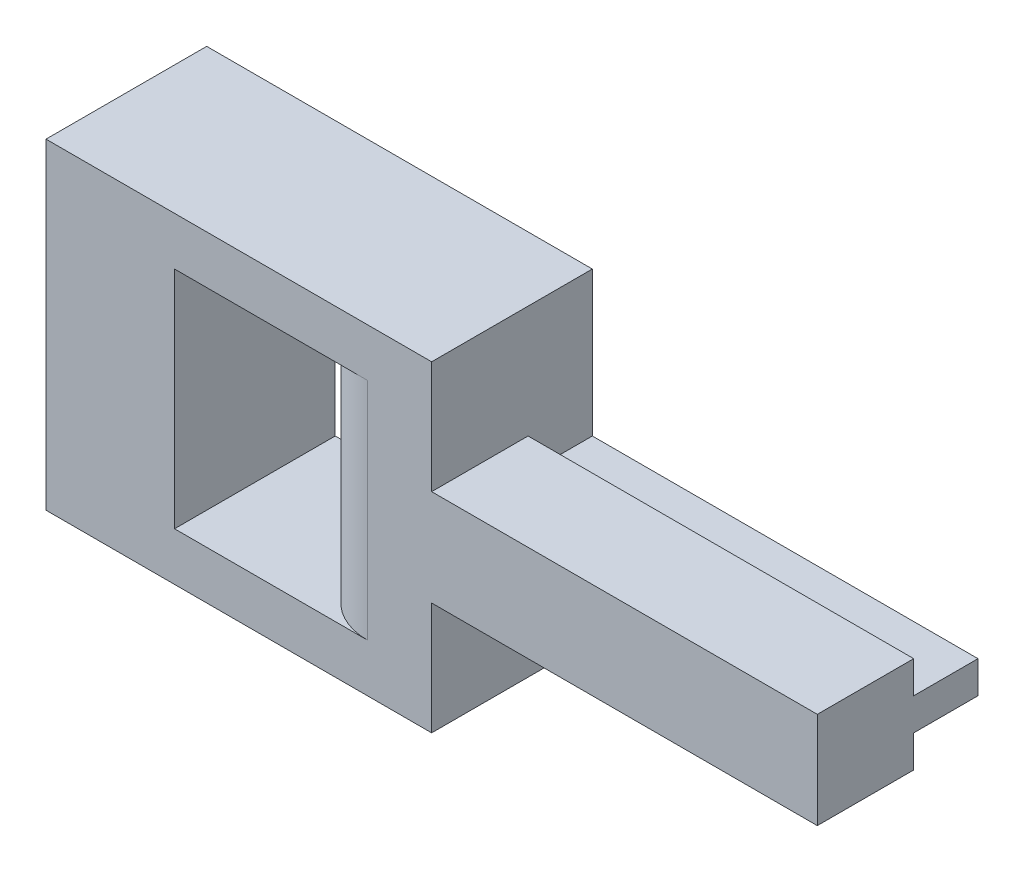
SolidWorks part; units mm, degrees
ref_plane "Plano frontal" through (0, 0, 0) normal (0, 0, 1) x (1, 0, 0)
ref_plane "Plano superior" through (0, 0, 0) normal (0, 1, 0) x (1, 0, 0)
ref_plane "Plano direito" through (0, 0, 0) normal (1, 0, 0) x (0, 0, -1)
sketch "Esboço1" plane through (0, 0, 0) normal (0, 0, 1) x (1, 0, 0)
  line L0 (4, 1.5) -> (8, 1.5)
  line L1 (24, 3.5) -> (24, 6.5)
  line L2 (4, 8.5) -> (8, 8.5)
  line L3 (8, 8.5) -> (8, 1.5)
  line L4 (0, 0) -> (12, 0)
  line L5 (4, 1.5) -> (4, 8.5)
  line L6 (12, 10) -> (0, 10)
  line L7 (0, 10) -> (0, 0)
  line L8 (12, 0) -> (12, 3.5)
  line L9 (12, 3.5) -> (24, 3.5)
  line L10 (12, 6.5) -> (12, 10)
  line L11 (12, 6.5) -> (24, 6.5)
  line L12 (24, 5) -> (9.8395, 5) construction
  point P1 (0, 5)
  point P19 (4, 5)
  dimension "D1" = 12
  dimension "D2" = 4
  dimension "D3" = 4
  dimension "D4" = 10
  dimension "D5" = 7
  dimension "D6" = 4
  dimension "D7" = 3
extrude "Ressalto-extrusão1" add sketch "Esboço1" along normal blind 5
fillet "Filete1" radius 2 1 edges at (8, 5, 5)
sketch "Esboço4" plane through (24, 0, 0) normal (1, 0, 0) x (0, 0, -1)
  line L0 (-2, 3.5) -> (-2, 4.5)
  line L1 (-5, 3.5) -> (0, 3.5) construction
  line L2 (-2, 4.5) -> (0, 4.5)
  line L3 (0, 3.5) -> (0, 6.5) construction
  line L4 (0, 5.5) -> (-2, 5.5)
  line L5 (-2, 5.5) -> (-2, 6.5)
  line L6 (-5, 6.5) -> (0, 6.5) construction
  line L7 (0, 5) -> (-2.0985, 5) construction
  line L8 (-2, 3.5) -> (-5, 3.5) construction
  line L9 (-5, 3.5) -> (-5, 6.5) construction
  line M5 (0, 3.5) -> (0, 6.5)
  line M6 (0, 6.5) -> (-5, 6.5)
  line M8 (-5, 3.5) -> (0, 3.5)
  dimension "D2" = 1
extrude "Corte-extrusão2" cut sketch "Esboço4" against normal up to surface (12 mm away) contours L2 L0 M8 M5 | L5 L4 M5 M6 up to face at (12, 1.75, 2.5)
